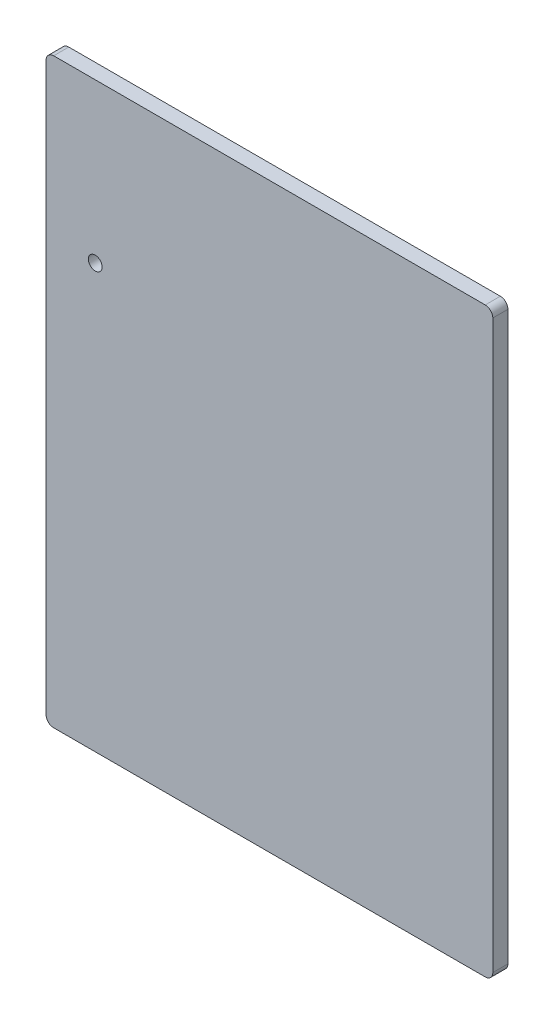
SolidWorks part; units mm, degrees
ref_plane "前视基准面" through (0, 0, 0) normal (0, 0, 1) x (1, 0, 0)
ref_plane "上视基准面" through (0, 0, 0) normal (0, 1, 0) x (1, 0, 0)
ref_plane "右视基准面" through (0, 0, 0) normal (1, 0, 0) x (0, 0, -1)
other "Configuration Table"
sketch "草图1" plane through (0, 0, 0) normal (0, 0, 1) x (1, 0, 0)
  line L1 (-295.5, 770) -> (295.5, 770)
  line L2 (-295.5, 770) -> (-295.5, 0)
  line L3 (-295.5, 0) -> (295.5, 0)
  line L4 (295.5, 770) -> (295.5, 0)
  point P4 (0, 0)
  dimension "D1" = 770
  dimension "D2" = 591
extrude "凸台-拉伸1" add sketch "草图1" along normal blind 20
sketch "草图2" plane through (0, 0, 20) normal (0, 0, 1) x (1, 0, 0)
  line L0 (-295.5, 770) -> (-295.5, 0) construction
  line L1 (295.5, 770) -> (-295.5, 770) construction
  circle A0 centre (-230.5, 560) radius 9.1
  dimension "D1" = 18.2
  dimension "D2" = 65
  dimension "D3" = 210
extrude "切除-拉伸1" cut sketch "草图2" against normal through all both and the other way through all
sketch "草图3" plane through (0, 0, 0) normal (0, 0, -1) x (-1, 0, 0)
  line L0 (-295.5, 0) -> (-295.5, 770) construction
  line L1 (-265.5, 121.5508) -> (-265.5, 70.0508) construction
  line L2 (-270.5, 95.8008) -> (-265.5, 95.8008)
  circle A0 centre (-270.5, 95.8008) radius 20
  circle A1 centre (-265.5, 121.5508) radius 2
  circle A2 centre (-265.5, 70.0508) radius 2
  point P8 (-265.5, 95.8008)
  dimension "D1" = 40
  dimension "D2" = 25
  dimension "D3" = 51.5
  dimension "D4" = 4
  dimension "D5" = 5
extrude "切除-拉伸2" [suppressed] cut sketch "草图3" against normal blind 10
fillet "圆角1" radius 10 4 edges at (-295.5, 770, 10) (295.5, 0, 10) (-295.5, 0, 10) (295.5, 770, 10)
sketch "草图4" plane through (0, 0, 0) normal (0, 0, -1) x (-1, 0, 0)
  line L0 (-275.485, 700) -> (-265.5, 700) construction
  line L1 (-285.5, 770) -> (285.5, 770) construction
  line L2 (-265.5, 310) -> (-275.485, 310) construction
  line L3 (-265.5, 100) -> (-292.9632, 100) construction
  line L4 (-295.5, 10) -> (-295.5, 760) construction
  circle A0 centre (-265.5, 700) radius 20.1
  circle A1 centre (-265.5, 310) radius 20.1
  circle A2 centre (-265.5, 100) radius 20.1
  dimension "D2" = 460
  dimension "D4" = 670
  dimension "D5" = 30
  dimension "D6" = 40.2
  dimension "D1" = 70
  dimension "D3" = 27.4632
extrude "切除-拉伸3" cut sketch "草图4" against normal blind 15
sketch "草图5" plane through (0, 0, 0) normal (0, 0, -1) x (-1, 0, 0)
  line L0 (0, 770) -> (0, 0) construction
  line L1 (-215.5, 740) -> (215.5, 740)
  line L2 (-215.5, 740) -> (-215.5, 30)
  line L3 (-215.5, 30) -> (215.5, 30)
  line L4 (215.5, 740) -> (215.5, 30)
  line L5 (-285.5, 770) -> (285.5, 770) construction
  line L6 (-295.5, 385) -> (295.5, 385) construction
  line L7 (-295.5, 10) -> (-295.5, 760) construction
  line L8 (295.5, 760) -> (295.5, 10) construction
  line L9 (-285.5, 770) -> (285.5, 770) construction
  dimension "D1" = 30
  dimension "D2" = 80
extrude "切除-拉伸4" cut sketch "草图5" against normal blind 5
fillet "圆角2" radius 16 4 edges at (-215.5, 30, 2.5) (-215.5, 740, 2.5) (215.5, 30, 2.5) (215.5, 740, 2.5)
